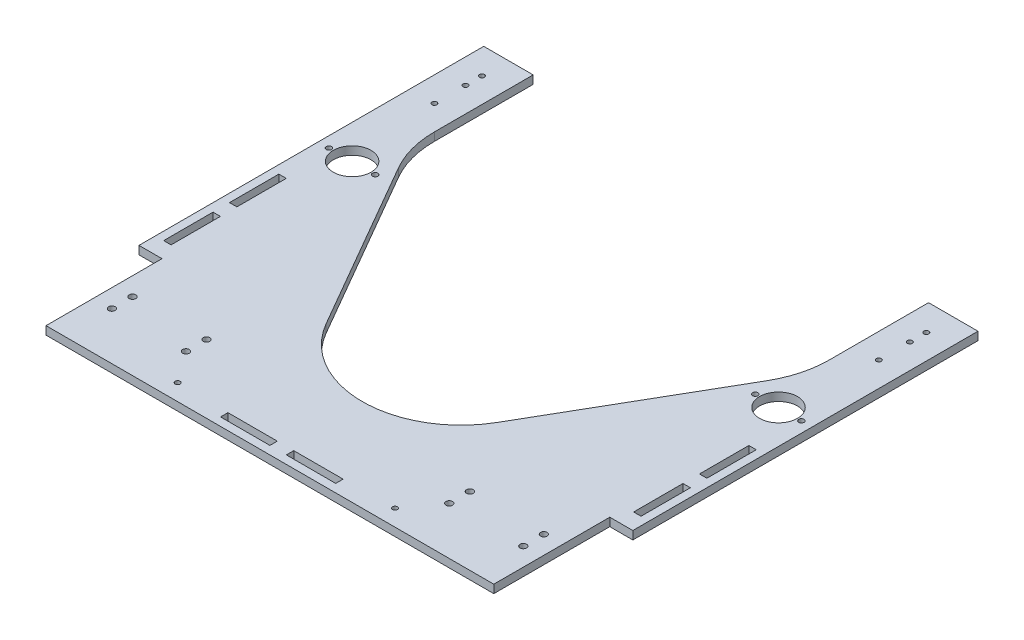
SolidWorks part; units mm, degrees
ref_plane "Front Plane" through (0, 0, 0) normal (0, 0, 1) x (1, 0, 0)
ref_plane "Top Plane" through (0, 0, 0) normal (0, 1, 0) x (1, 0, 0)
ref_plane "Right Plane" through (0, 0, 0) normal (1, 0, 0) x (0, 0, -1)
sketch "Sketch2" plane through (0, 0, 0) normal (0, 1, 0) x (1, 0, 0)
  line L0 (-120, 42.727) -> (-120, 102.6707)
  line L4 (0, -61.2594) -> (0, 49938.7406) construction
  line L5 (-51.9615, -91.1961) -> (-111.9615, 12.727) construction
  line L7 (-135.0279, 102.6707) -> (-135.0279, -49897.3293) construction
  line L8 (51.9615, -91.1961) -> (111.9615, 12.727) construction
  line L10 (51.9615, -91.1961) -> (111.9615, 12.727)
  line L11 (-111.9615, 12.727) -> (-51.9615, -91.1961)
  line L14 (150, -14.8318) -> (150.0558, 2.1045)
  line L15 (120, 35.7608) -> (120, 87.6049) construction
  line L17 (120, 87.6049) -> (120, 42.727)
  line L19 (-136.0558, -177.3293) -> (136.0558, -177.3293)
  line L21 (-150.0558, 102.6426) -> (150.0558, 102.924) construction
  line L35 (119.5942, 35.7608) -> (120, 35.7608) construction
  line L36 (135.0279, 102.924) -> (135.0279, 50102.924) construction
  line L37 (-150.0558, 2.1045) -> (-109.056, 2.1045) construction
  line L38 (-129.5558, 22.7012) -> (-129.5558, -18.2988) construction
  line L39 (150.0558, 2.1045) -> (109.056, 2.1045) construction
  line L40 (129.5558, 22.7012) -> (129.5558, -18.2988) construction
  line L41 (-136.0558, -142.0793) -> (136.0558, -142.0793) construction
  line L42 (-150.0558, -106.8293) -> (-136.0558, -106.8293)
  line L45 (-136.0558, -106.8293) -> (-136.0558, -177.3293)
  line L47 (136.0558, -177.3293) -> (136.0558, -106.8293)
  line L48 (136.0558, -106.8293) -> (150.0558, -106.8293)
  line L52 (-150.0558, 102.6707) -> (-120, 102.6707)
  line L54 (150.0558, 102.924) -> (150.0558, -106.8293)
  line L56 (120, 87.6049) -> (120, 102.924)
  line L57 (120, 102.924) -> (150.0558, 102.924)
  line L59 (-150.0558, 102.6707) -> (-150.0558, -106.8293)
  line L60 (-5, -172.3293) -> (-35, -172.3293)
  line L61 (5, -167.8293) -> (35, -167.8293)
  line L62 (5, -167.8293) -> (5, -172.3293)
  line L63 (5, -172.3293) -> (35, -172.3293)
  line L64 (35, -167.8293) -> (35, -172.3293)
  line L65 (-35, -167.8293) -> (-35, -172.3293)
  line L66 (-5, -167.8293) -> (-5, -172.3293)
  line L67 (-5, -167.8293) -> (-35, -167.8293)
  line L68 (135.0279, -61.8293) -> (50135.0279, -61.8293) construction
  line L69 (140.5558, -96.8293) -> (145.0558, -96.8293)
  line L70 (140.5558, -96.8293) -> (140.5558, -66.8293)
  line L71 (140.5558, -66.8293) -> (145.0558, -66.8293)
  line L72 (145.0558, -96.8293) -> (145.0558, -66.8293)
  line L73 (140.5558, -96.8293) -> (145.0558, -66.8293) construction
  line L74 (140.5558, -66.8293) -> (145.0558, -96.8293) construction
  line L75 (140.5558, -56.8293) -> (145.0558, -56.8293)
  line L76 (145.0558, -26.8293) -> (145.0558, -56.8293)
  line L77 (140.5558, -26.8293) -> (145.0558, -26.8293)
  line L78 (140.5558, -26.8293) -> (140.5558, -56.8293)
  line L79 (-140.5558, -66.8293) -> (-145.0558, -66.8293)
  line L80 (-145.0558, -96.8293) -> (-145.0558, -66.8293)
  line L81 (-140.5558, -96.8293) -> (-145.0558, -96.8293)
  line L82 (-140.5558, -96.8293) -> (-140.5558, -66.8293)
  line L83 (-140.5558, -26.8293) -> (-140.5558, -56.8293)
  line L84 (-140.5558, -26.8293) -> (-145.0558, -26.8293)
  line L85 (-145.0558, -26.8293) -> (-145.0558, -56.8293)
  line L86 (-140.5558, -56.8293) -> (-145.0558, -56.8293)
  arc A0 (-51.9615, -91.1961) -> (51.9615, -91.1961) centre (0, -61.1961) ccw
  arc A1 (-120, 42.727) -> (-111.9615, 12.727) centre (-60, 42.727) ccw
  arc A2 (111.9615, 12.727) -> (120, 42.727) centre (60, 42.727) ccw
  circle A8 centre (0, -61.1961) radius 60 construction
  circle A9 centre (-60, 42.727) radius 60 construction
  circle A10 centre (60, 42.727) radius 60 construction
  circle A11 centre (-129.5558, 2.2012) radius 20.5 construction
  circle A12 centre (129.5558, 2.2012) radius 20.5 construction
  circle A13 centre (-143.5558, 2.1045) radius 1.625
  circle A14 centre (-115.5, 2.1045) radius 1.625
  circle A15 centre (115.5, 2.1045) radius 1.625
  circle A16 centre (143.5558, 2.1045) radius 1.625
  circle A17 centre (129.5558, 2.2012) radius 11.5
  circle A18 centre (-129.5558, 2.2012) radius 11.5
  circle A19 centre (-125, -135.8293) radius 2
  circle A20 centre (-125, -148.3293) radius 2
  circle A21 centre (-80, -135.8293) radius 2
  circle A22 centre (-80, -148.3293) radius 2
  circle A23 centre (80, -135.8293) radius 2
  circle A24 centre (80, -148.3293) radius 2
  circle A25 centre (125, -148.3293) radius 2
  circle A26 centre (125, -135.8293) radius 2
  circle A27 centre (-135.0279, 86.5707) radius 1.5
  circle A28 centre (-135.0279, 76.5707) radius 1.5
  circle A29 centre (135.0279, 76.5707) radius 1.5
  circle A30 centre (135.0279, 86.5707) radius 1.5
  circle A31 centre (-135.0279, 57.6707) radius 1.5
  circle A32 centre (135.0279, 57.6707) radius 1.5
  circle A33 centre (66.0558, -167.3293) radius 1.5
  circle A34 centre (-66.0558, -167.3293) radius 1.5
  point P9 (-135.0279, 102.6707)
  point P13 (0, -121.1961)
  point P15 (111.9615, 12.727)
  point P20 (-111.9615, 12.727)
  point P21 (-51.9615, -91.1961)
  point P22 (-143.5558, 2.1045)
  point P24 (-115.5, 2.1045)
  point P27 (51.9615, -91.1961)
  point P36 (0, -177.3293)
  point P40 (60, 102.727)
  point P46 (-135.0279, 57.6707)
  point P56 (115.5, 2.1045)
  point P58 (143.5558, 2.1045)
  point P76 (-125.0558, -142.0793)
  point P100 (135.0279, 102.924)
  point P101 (66.0558, -167.3293)
  point P114 (142.8058, -81.8293)
  dimension "D1" = 120
  dimension "D2" = 280
  dimension "D3" = 14.6
  dimension "D7" = 3.25
  dimension "D5" = 41
  dimension "D6" = 3
  dimension "D11" = 23
  dimension "D14" = 4
  dimension "D15" = 45
  dimension "D4" = 10
  dimension "D16" = 3
  dimension "D21" = 3
  dimension "D22" = 5
  dimension "D8" = 70.5
  dimension "D9" = 14
  dimension "D10" = 45
  dimension "D12" = 11
  dimension "D13" = 12.5
  dimension "D17" = 15.0279
  dimension "D18" = 15.0279
  dimension "D19" = 70
  dimension "D20" = 10
  dimension "D23" = 30
  dimension "D24" = 5
  dimension "D25" = 4.5
  dimension "D26" = 4.5
  dimension "D27" = 30
  dimension "D28" = 5
  dimension "D29" = 10
  dimension "D30" = 5
extrude "Boss-Extrude1" add sketch "Sketch2" along normal blind 5
